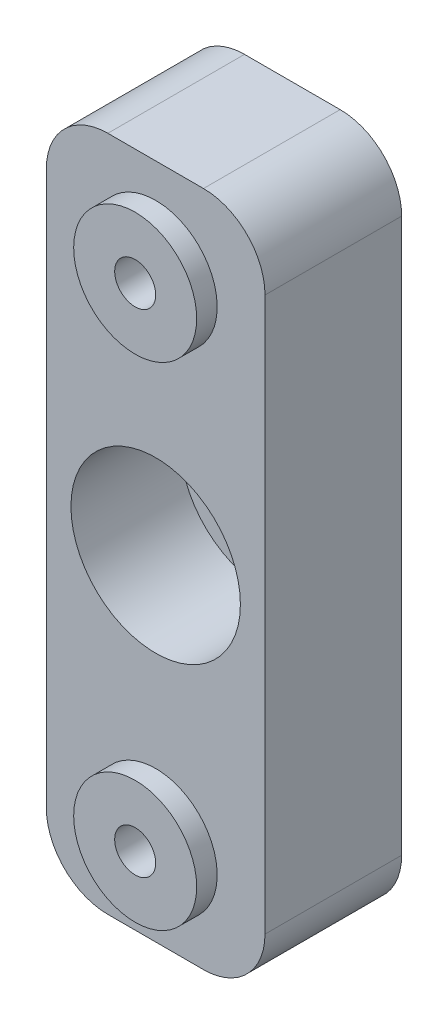
SolidWorks part; units mm, degrees
ref_plane "Alzado" through (0, 0, 0) normal (0, 0, 1) x (1, 0, 0)
ref_plane "Planta" through (0, 0, 0) normal (0, 1, 0) x (1, 0, 0)
ref_plane "Vista lateral" through (0, 0, 0) normal (1, 0, 0) x (0, 0, -1)
sketch "Croquis1" plane through (0, 0, 0) normal (0, 0, -1) x (-1, 0, 0)
  line L1 (-11.5, 55) -> (-4.5, 55)
  line L2 (-16, 50.5) -> (-16, 10)
  line L3 (-11.5, 5.5) -> (-4.5, 5.5)
  line L4 (0, 50.5) -> (0, 10)
  arc A0 (-16, 10) -> (-11.5, 5.5) centre (-11.5, 10) ccw
  arc A1 (-4.5, 5.5) -> (0, 10) centre (-4.5, 10) ccw
  arc A2 (-4.5, 55) -> (0, 50.5) centre (-4.5, 50.5) cw
  arc A3 (-11.5, 55) -> (-16, 50.5) centre (-11.5, 50.5) ccw
  point P6 (-16, 5.5)
  point P11 (0, 55)
  point P17 (-16, 55)
  dimension "D3" = 4.5
  dimension "D1" = 49.5
  dimension "D2" = 16
extrude "Saliente-Extruir1" add sketch "Croquis1" against normal blind 10 separate body
sketch "Croquis2" plane through (0, 0, 0) normal (0, 0, -1) x (-1, 0, 0)
  line L0 (-8, 51.5) -> (-11.0311, 49.75)
  line L1 (-11.0311, 49.75) -> (-11.0311, 46.25)
  line L2 (-11.0311, 46.25) -> (-8, 44.5)
  line L3 (-8, 44.5) -> (-4.9689, 46.25)
  line L4 (-4.9689, 46.25) -> (-4.9689, 49.75)
  line L5 (-4.9689, 49.75) -> (-8, 51.5)
  line L6 (-8, 15.5) -> (-11.0311, 13.75)
  line L7 (-11.0311, 13.75) -> (-11.0311, 10.25)
  line L8 (-11.0311, 10.25) -> (-8, 8.5)
  line L9 (-8, 8.5) -> (-4.9689, 10.25)
  line L10 (-4.9689, 10.25) -> (-4.9689, 13.75)
  line L11 (-4.9689, 13.75) -> (-8, 15.5)
  line L12 (0, 10) -> (0, 50.5) construction
  line L13 (-11.5, 5.5) -> (-4.5, 5.5) construction
  dimension "D1" = 4.9689
  dimension "D2" = 8
  dimension "D3" = 8.25
  dimension "D4" = 40.75
extrude "Cortar-Extruir2" cut sketch "Croquis2" against normal blind 2.5
sketch "Croquis3" plane through (0, 0, 10) normal (0, 0, 1) x (1, 0, 0)
  line L0 (16, 50.5) -> (16, 10) construction
  line L1 (4.5, 55) -> (11.5, 55) construction
  circle A0 centre (8, 48) radius 4.5
  circle A1 centre (8, 12) radius 4.5
  dimension "D1" = 9
  dimension "D2" = 8
  dimension "D3" = 7
  dimension "D4" = 43
extrude "Saliente-Extruir2" add sketch "Croquis3" along normal blind 1.5
sketch "Croquis4" plane through (0, 0, 2.5) normal (0, 0, -1) x (-1, 0, 0)
  line L0 (-11.0311, 49.75) -> (-11.0311, 46.25) construction
  circle A0 centre (-8, 48) radius 1.5
  circle A1 centre (-8, 12) radius 1.5
  dimension "D1" = 3
  dimension "D2" = 3.0311
  dimension "D3" = 1.75
  dimension "D4" = 34.25
extrude "Cortar-Extruir3" cut sketch "Croquis4" against normal through all
sketch "Croquis5" plane through (0, 0, 10) normal (0, 0, 1) x (1, 0, 0)
  line L0 (16, 50.5) -> (16, 10) construction
  circle A0 centre (8, 30) radius 6.2
  dimension "D1" = 12.4
  dimension "D2" = 8
  dimension "D3" = 25
extrude "Cortar-Extruir4" cut sketch "Croquis5" against normal blind 8
